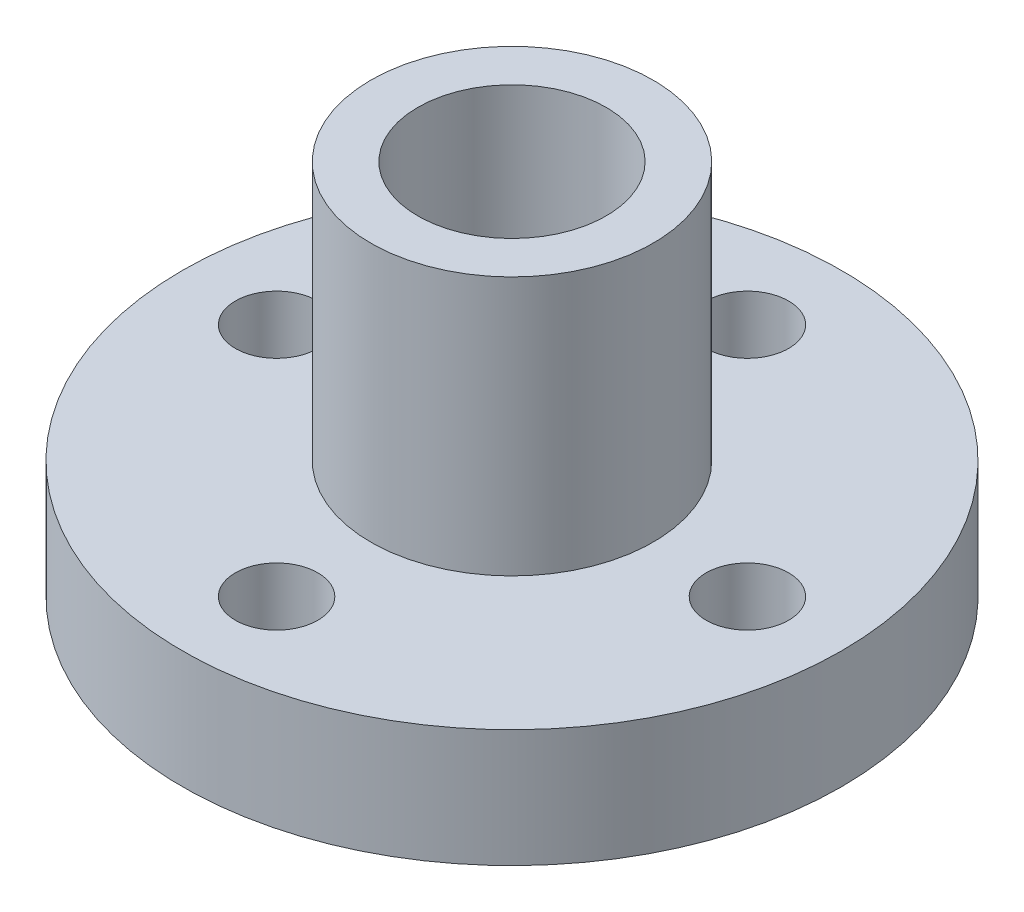
SolidWorks part; units mm, degrees
ref_plane "前视基准面" through (0, 0, 0) normal (0, 0, 1) x (1, 0, 0)
ref_plane "上视基准面" through (0, 0, 0) normal (0, 1, 0) x (1, 0, 0)
ref_plane "右视基准面" through (0, 0, 0) normal (1, 0, 0) x (0, 0, -1)
sketch "草图1" plane through (0, 0, 0) normal (0, 0, 1) x (1, 0, 0)
  line L0 (-4, -1.8133) -> (-14, -1.8133)
  line L1 (-14, -1.8133) -> (-14, 3.1867)
  line L2 (-14, 3.1867) -> (-6, 3.1867)
  line L3 (-6, 3.1867) -> (-6, 14.1867)
  line L4 (-6, 14.1867) -> (-4, 14.1867)
  line L5 (-4, 14.1867) -> (-4, -1.8133)
  line L6 (0, 8.12) -> (0, 0) construction
  point P9 (0, 0)
  dimension "D1" = 2
  dimension "D2" = 12
  dimension "D3" = 5
  dimension "D4" = 16
  dimension "D5" = 28
  dimension "D6" = 8
revolve "旋转1" add sketch "草图1" angle 360 about L6
sketch "草图2" plane through (0, 3.1867, 0) normal (0, 1, 0) x (1, 0, 0)
  circle A0 centre (0, 10) radius 1.75
  circle A1 centre (10, 0) radius 1.75
  circle A2 centre (0, -10) radius 1.75
  circle A3 centre (-10, 0) radius 1.75
  point P12 (0, 0)
  dimension "D1" = 3.5
  dimension "D2" = 10
  dimension "D3" = 4
extrude "切除-拉伸1" cut sketch "草图2" against normal through all
